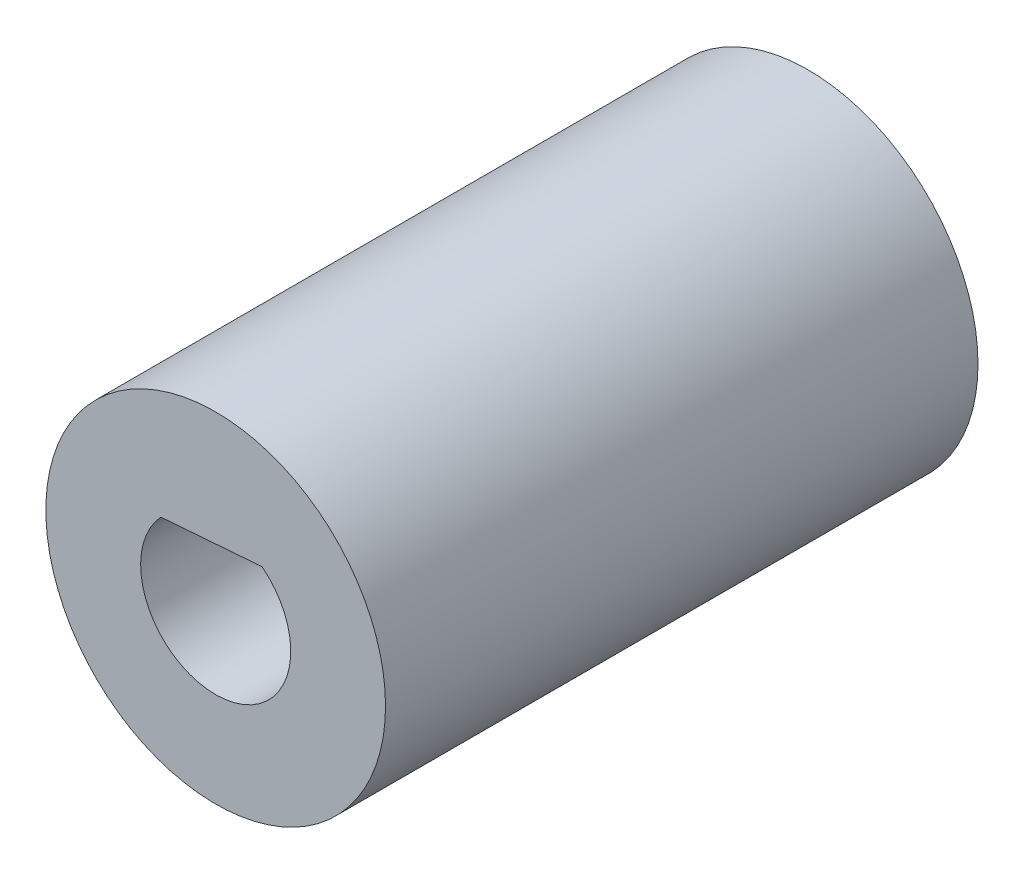
SolidWorks part; units mm, degrees
ref_plane "Front Plane" through (0, 0, 0) normal (0, 0, 1) x (1, 0, 0)
ref_plane "Top Plane" through (0, 0, 0) normal (0, 1, 0) x (1, 0, 0)
ref_plane "Right Plane" through (0, 0, 0) normal (1, 0, 0) x (0, 0, -1)
sketch "Sketch1" plane through (0, 0, 0) normal (0, 0, 1) x (1, 0, 0)
  line L0 (-1.3863, 1.2993) -> (1.1754, 1.4928)
  circle A0 centre (0, 0) radius 4.3
  arc A1 (-1.3863, 1.2993) -> (1.1754, 1.4928) centre (0, 0) ccw
  dimension "D1" = 8.6
  dimension "D2" = 3.8
  dimension "D3" = 3.3
extrude "Boss-Extrude1" add sketch "Sketch1" along normal blind 15
